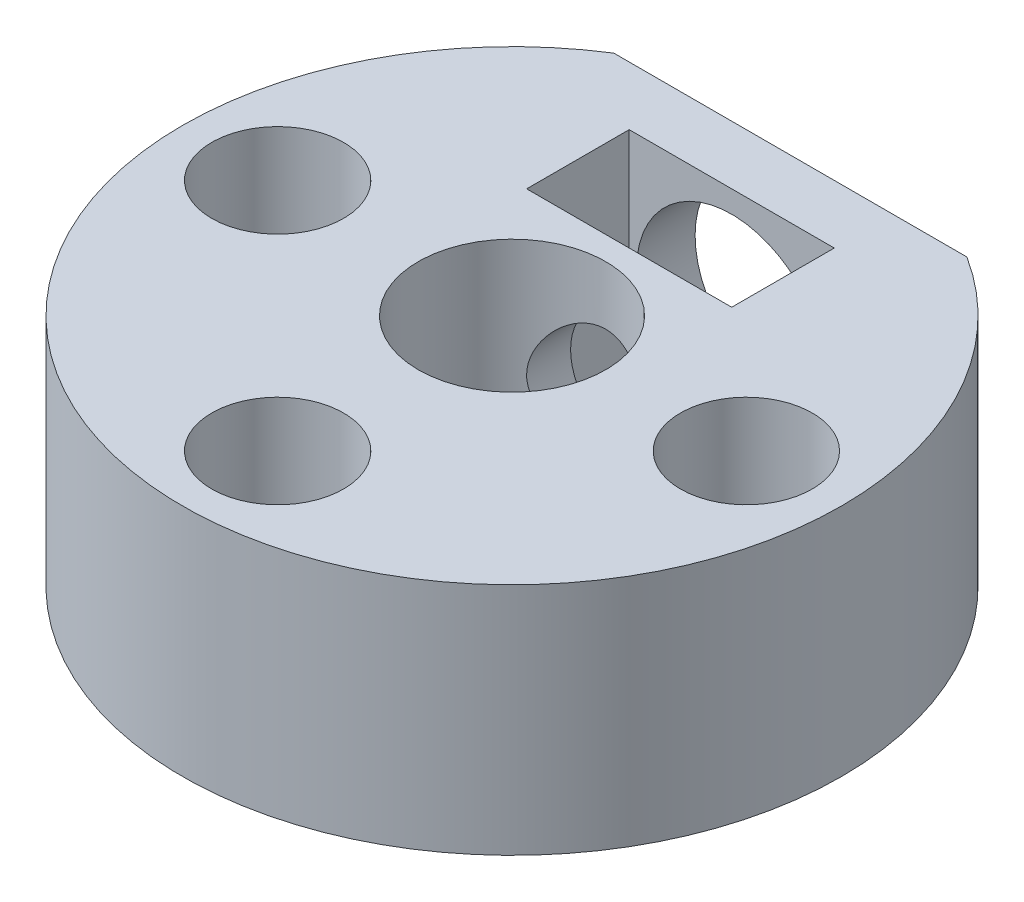
SolidWorks part; units mm, degrees
ref_plane "Plan de face" through (0, 0, 0) normal (0, 0, 1) x (1, 0, 0)
ref_plane "Plan de dessus" through (0, 0, 0) normal (0, 1, 0) x (1, 0, 0)
ref_plane "Plan de droite" through (0, 0, 0) normal (1, 0, 0) x (0, 0, -1)
sketch "Esquisse1" plane through (0, 0, 0) normal (0, 1, 0) x (1, 0, 0)
  line L4 (6.026, 9.5) -> (-6.026, 9.5)
  arc A0 (-6.026, 9.5) -> (6.026, 9.5) centre (0, 0) ccw
  dimension "D1" = 22.5
  dimension "D4" = 9.5
extrude "Boss.-Extru.1" add sketch "Esquisse1" along normal blind 8
sketch "Sketch1" plane through (0, 8, 0) normal (0, 1, 0) x (1, 0, 0)
  circle A0 centre (0, 0) radius 3.2
  dimension "D1" = 6.4
extrude "Cut-Extrude1" cut sketch "Sketch1" against normal through all
sketch "Esquisse7" plane through (0, 8, 0) normal (0, 1, 0) x (1, 0, 0)
  line L1 (-3.5, 4) -> (3.5, 4)
  line L2 (-3.5, 4) -> (-3.5, 7.5)
  line L3 (-3.5, 7.5) -> (3.5, 7.5)
  line L4 (3.5, 4) -> (3.5, 7.5)
  line L5 (-3.5, 4) -> (3.5, 7.5) construction
  line L6 (-3.5, 7.5) -> (3.5, 4) construction
  point P0 (0, 5.75)
  dimension "D3" = 4
  dimension "D1" = 3.5
  dimension "D2" = 7
extrude "Enlèv. mat.-Extru.2" cut sketch "Esquisse7" against normal through all
sketch "Esquisse8" plane through (0, 0, 0) normal (0, -1, 0) x (1, 0, 0)
  line L0 (-6.026, -9.5) -> (6.026, -9.5)
  line L1 (6.026, -9.5) -> (-6.026, -9.5) construction
  arc A0 (6.026, -9.5) -> (-6.026, -9.5) centre (0, 0) ccw
extrude "Boss.-Extru.2" [suppressed] add sketch "Esquisse8" along normal blind 3
hole_wizard "Chambrage pour vis à tête cylindrique à 6 pans creux (ou vis CHC) M21" positions "Esquisse12" profile "Esquisse13" counterbore size "M2" standard "Ansi Metric" end condition through all
sketch "Esquisse12" plane through (0, 8, 0) normal (0, 1, 0) x (1, 0, 0)
  line L0 (-8, 0) -> (0, 0) construction
  line L1 (0, 0) -> (0, -8) construction
  line L3 (0, 0) -> (8, 0) construction
  point P0 (-8, 0)
  point P2 (0, -8)
  point P4 (8, 0)
  dimension "D1" = 8
sketch "Esquisse13" plane through (-8, 8, 0) normal (1, 0, 0) x (0, 0, 1)
  line L0 (0, 0) -> (0, 8)
  line L1 (0, 8) -> (1.25, 8)
  line L3 (1.25, 8) -> (1.25, 5.3)
  line L4 (1.25, 5.3) -> (2.25, 5.3)
  line L5 (2.25, 5.3) -> (2.25, 0)
  line L7 (2.25, 0) -> (0, 0)
  line L11 (0, -6.35) -> (0, 107.95) construction
  dimension "Diamètre du perçage jusqu'au prochain" = 2.5
  dimension "Profondeur du perçage jusqu'au prochain" = 8
  dimension "Diamètre du chambrage" = 4.5
  dimension "Profondeur du chambrage" = 5.3
sketch "Esquisse14" [suppressed] plane through (0, -3, 0) normal (0, -1, 0) x (1, 0, 0)
  circle A0 centre (0, 0) radius 4.25
  dimension "D1" = 8.5
extrude "Enlèv. mat.-Extru.3" [suppressed] cut sketch "Esquisse14" against normal blind 2
hole_wizard "CBORE for M5 Hex Head Bolt1" positions "Sketch2" profile "Sketch3" counterbore size "M5" standard "ANSI Metric"
sketch "Sketch2" plane through (0, 0, -9.5) normal (0, 0, -1) x (-1, 0, 0)
  point P0 (0, 4)
  point P8 (0, 0)
  dimension "D1" = 4
sketch "Sketch3" plane through (0, 4, -9.5) normal (1, 0, 0) x (0, 1, 0)
  line L0 (0, 0) -> (0, 10.7007)
  line L1 (0, 10.7007) -> (2, 9.499)
  line L2 (2, 9.499) -> (2, 2)
  line L3 (2, 2) -> (3.25, 2)
  line L4 (3.25, 2) -> (3.25, 0)
  line L5 (3.25, 0) -> (0, 0)
  line L10 (0, 10.7007) -> (-2, 9.499) construction
  line L11 (0, -6.35) -> (0, 107.95) construction
  dimension "Hole Dia." = 4
  dimension "Hole Depth" = 9.499
  dimension "C'Bore Dia." = 6.5
  dimension "C'Bore Depth" = 2
  dimension "Drill Angle" = 118
